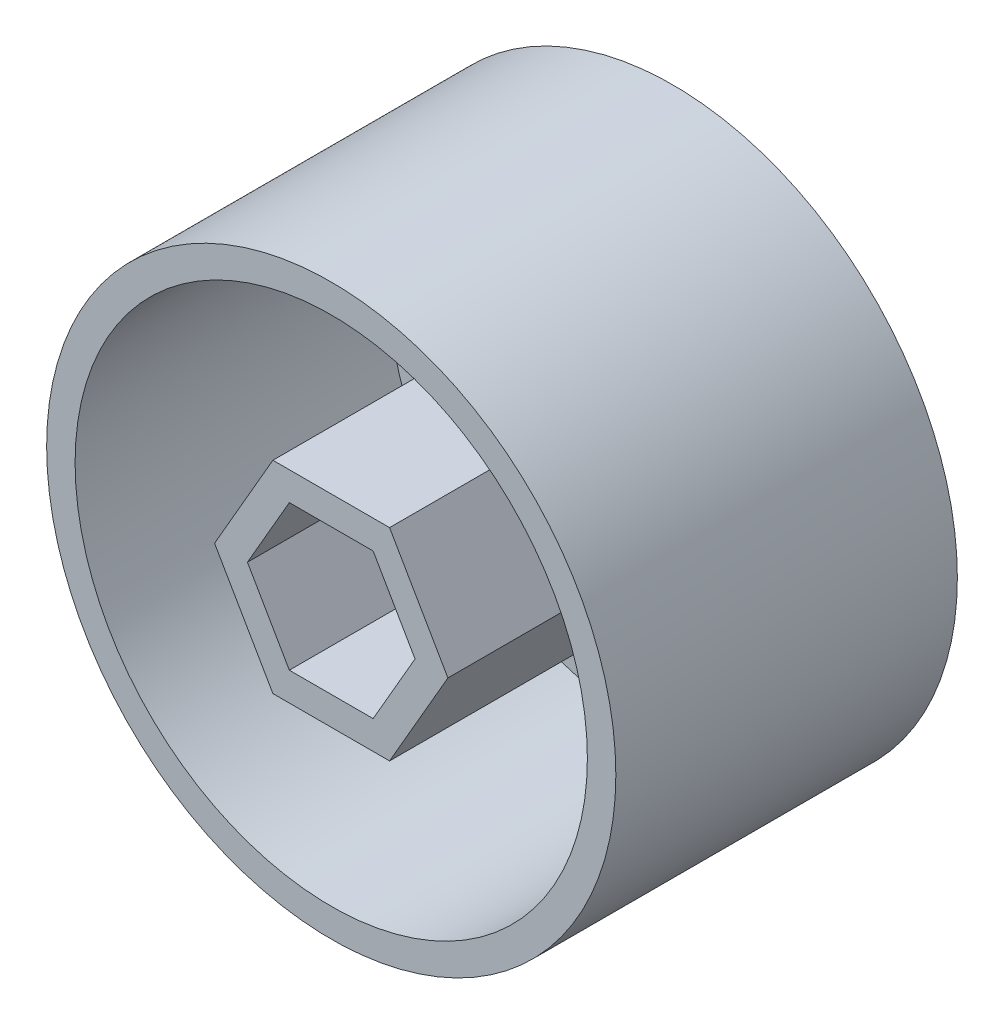
SolidWorks part; units mm, degrees
ref_plane "前视基准面" through (0, 0, 0) normal (0, 0, 1) x (1, 0, 0)
ref_plane "上视基准面" through (0, 0, 0) normal (0, 1, 0) x (1, 0, 0)
ref_plane "右视基准面" through (0, 0, 0) normal (1, 0, 0) x (0, 0, -1)
sketch "草图1" plane through (0, 0, 0) normal (0, 0, 1) x (1, 0, 0)
  line L0 (4.0992, 7.1) -> (-4.0992, 7.1)
  line L1 (5.889, 0) -> (2.9445, 5.1)
  line L2 (2.9445, 5.1) -> (-2.9445, 5.1)
  line L3 (-2.9445, 5.1) -> (-5.889, 0)
  line L4 (-5.889, 0) -> (-2.9445, -5.1)
  line L5 (-2.9445, -5.1) -> (2.9445, -5.1)
  line L6 (2.9445, -5.1) -> (5.889, 0)
  line L7 (-4.0992, 7.1) -> (-8.1984, 0)
  line L8 (-8.1984, 0) -> (-4.0992, -7.1)
  line L9 (-4.0992, -7.1) -> (4.0992, -7.1)
  line L10 (4.0992, -7.1) -> (8.1984, 0)
  line L11 (8.1984, 0) -> (4.0992, 7.1)
  circle A0 centre (0, 0) radius 20
  circle A1 centre (0, 0) radius 18
  circle A2 centre (0, 0) radius 5.1 construction
  dimension "D1" = 40
  dimension "D3" = 10.2
  dimension "D2" = 2
  dimension "D4" = 2
extrude "凸台-拉伸1" add sketch "草图1" along normal blind 24 contours A0 A1 | L10 L11 L0 L7 L8 L9 L6 L5 L4 L3 L2 L1
sketch "草图2" plane through (0, 0, 0) normal (0, 0, -1) x (-1, 0, 0)
  line L0 (2.9445, 5.1) -> (5.889, 0) construction
  line L1 (5.889, 0) -> (2.9445, -5.1) construction
  line L2 (2.9445, -5.1) -> (-2.9445, -5.1) construction
  line L3 (-2.9445, -5.1) -> (-5.889, 0) construction
  line L4 (-5.889, 0) -> (-2.9445, 5.1) construction
  line L5 (-2.9445, 5.1) -> (2.9445, 5.1) construction
  line L6 (2.9445, 5.1) -> (5.889, 0)
  line L7 (5.889, 0) -> (2.9445, -5.1)
  line L8 (2.9445, -5.1) -> (-2.9445, -5.1)
  line L9 (-2.9445, -5.1) -> (-5.889, 0)
  line L10 (-5.889, 0) -> (-2.9445, 5.1)
  line L11 (-2.9445, 5.1) -> (2.9445, 5.1)
  circle A0 centre (0, 0) radius 20
  dimension "D1" = 40
extrude "凸台-拉伸2" add sketch "草图2" against normal blind 2
ref_plane "基准面1" through (0, 0, 12) normal (0, 0, -1) x (-1, 0, 0)
